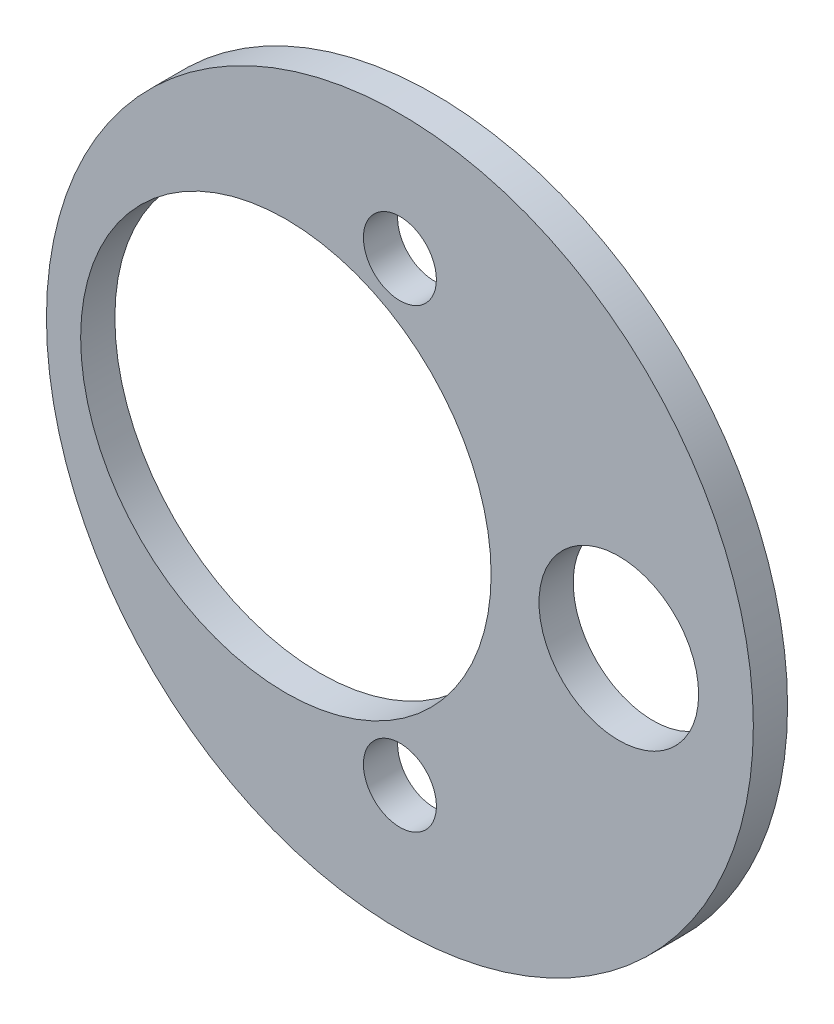
SolidWorks part; units mm, degrees
ref_plane "Спереди" through (0, 0, 0) normal (0, 0, 1) x (1, 0, 0)
ref_plane "Сверху" through (0, 0, 0) normal (0, 1, 0) x (1, 0, 0)
ref_plane "Справа" through (0, 0, 0) normal (1, 0, 0) x (0, 0, -1)
sketch "Эскиз1" plane through (0, 0, 0) normal (0, 0, 1) x (1, 0, 0)
  line L0 (-19.15, 0) -> (18.4889, 0) construction
  line L3 (0, 17.4039) -> (0, -17.1885) construction
  circle A23 centre (0, 0) radius 15.5
  circle A24 centre (-5, 0) radius 9
  circle A25 centre (9.6, 0) radius 3.5
  circle A26 centre (0, 10) radius 1.6
  circle A27 centre (0, -10) radius 1.6
  dimension "D1" = 31
  dimension "D2" = 5
  dimension "D3" = 18
  dimension "D6" = 3.2
  dimension "D7" = 10
  dimension "D5" = 7
  dimension "D4" = 9.6
extrude "Бобышка-Вытянуть1" add sketch "Эскиз1" along normal blind 1.5
